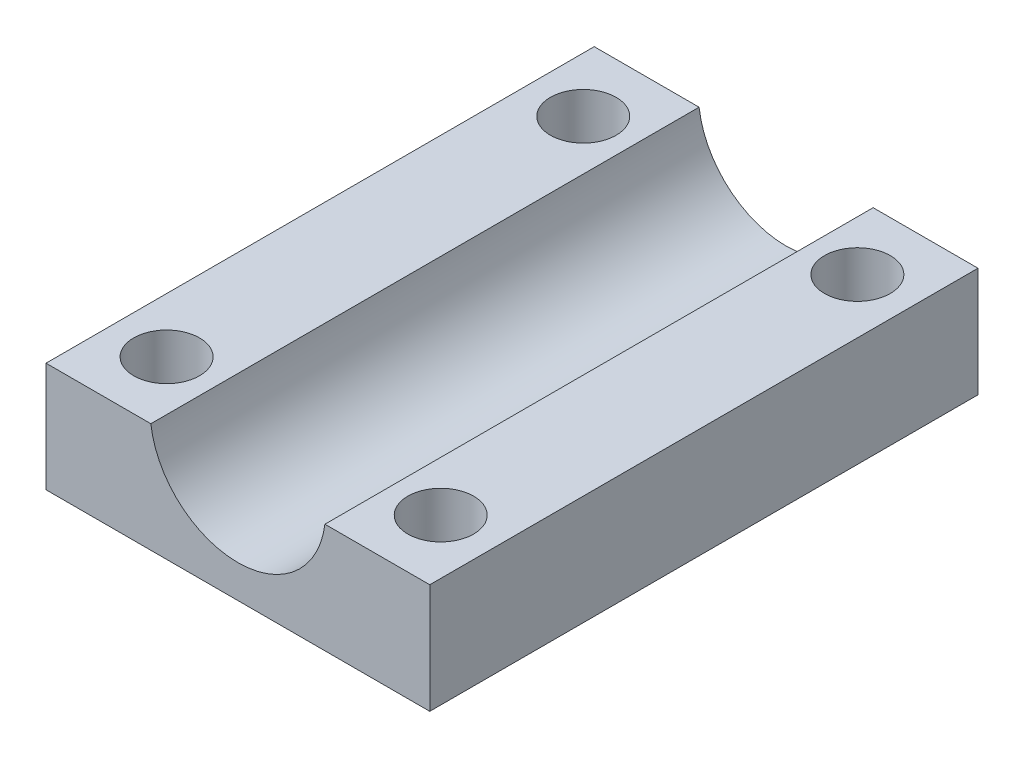
SolidWorks part; units mm, degrees
ref_plane "Front Plane" through (0, 0, 0) normal (0, 0, 1) x (1, 0, 0)
ref_plane "Top Plane" through (0, 0, 0) normal (0, 1, 0) x (1, 0, 0)
ref_plane "Right Plane" through (0, 0, 0) normal (1, 0, 0) x (0, 0, -1)
sketch "Sketch2" plane through (0, 0, 0) normal (0, 0, 1) x (1, 0, 0)
  line L1 (-17.5, -11.9286) -> (-7.9373, -11.9286)
  line L2 (-17.5, -11.9286) -> (-17.5, -21.9286)
  line L3 (-17.5, -21.9286) -> (17.5, -21.9286)
  line L4 (17.5, -11.9286) -> (17.5, -21.9286)
  line L7 (7.9373, -11.9286) -> (17.5, -11.9286)
  arc A0 (-7.9373, -11.9286) -> (7.9373, -11.9286) centre (0, -10.9286) ccw
  dimension "D3" = 8
  dimension "D1" = 10
extrude "Boss-Extrude1" add sketch "Sketch2" against normal blind 50
sketch "Sketch3" plane through (0, -21.9286, 0) normal (0, -1, 0) x (1, 0, 0)
  line L0 (0, 0) -> (0, -50) construction
  line L1 (-17.5, 0) -> (17.5, 0) construction
  line L2 (-17.5, -50) -> (17.5, -50) construction
  line L4 (-17.5, -50) -> (-17.5, 0) construction
  line L5 (-17.5, -25) -> (17.5, -25) construction
  line L6 (17.5, -50) -> (17.5, 0) construction
  circle A0 centre (12.5, -6) radius 3
  circle A1 centre (-12.5, -6) radius 3
  circle A2 centre (-12.5, -44) radius 3
  circle A3 centre (12.5, -44) radius 3
  dimension "D1" = 6
  dimension "D2" = 5
  dimension "D3" = 6
extrude "Cut-Extrude1" cut sketch "Sketch3" against normal through all
